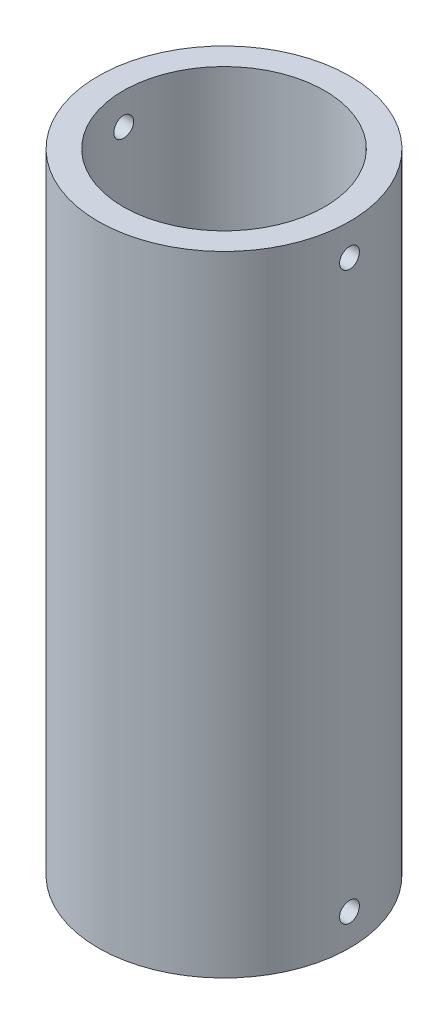
SolidWorks part; units mm, degrees
ref_plane "Front Plane" through (0, 0, 0) normal (0, 0, 1) x (1, 0, 0)
ref_plane "Top Plane" through (0, 0, 0) normal (0, 1, 0) x (1, 0, 0)
ref_plane "Right Plane" through (0, 0, 0) normal (1, 0, 0) x (0, 0, -1)
sketch "Sketch1" plane through (0, 0, 0) normal (0, 1, 0) x (1, 0, 0)
  circle A0 centre (0, 0) radius 20
  circle A1 centre (0, 0) radius 16
  dimension "D1" = 40
  dimension "D2" = 32
extrude "Boss-Extrude1" add sketch "Sketch1" along normal blind 100
sketch "Sketch2" plane through (0, 0, 0) normal (1, 0, 0) x (0, 0, -1)
  line L0 (20, 100) -> (-20, 100) construction
  line L1 (-20, 0) -> (20, 0) construction
  circle A0 centre (0, 95) radius 1.575
  circle A1 centre (0, 5) radius 1.575
  dimension "D1" = 3.15
  dimension "D2" = 3.15
  dimension "D3" = 5
  dimension "D4" = 5
extrude "Cut-Extrude1" cut sketch "Sketch2" against normal blind 46 and the other way blind 52
